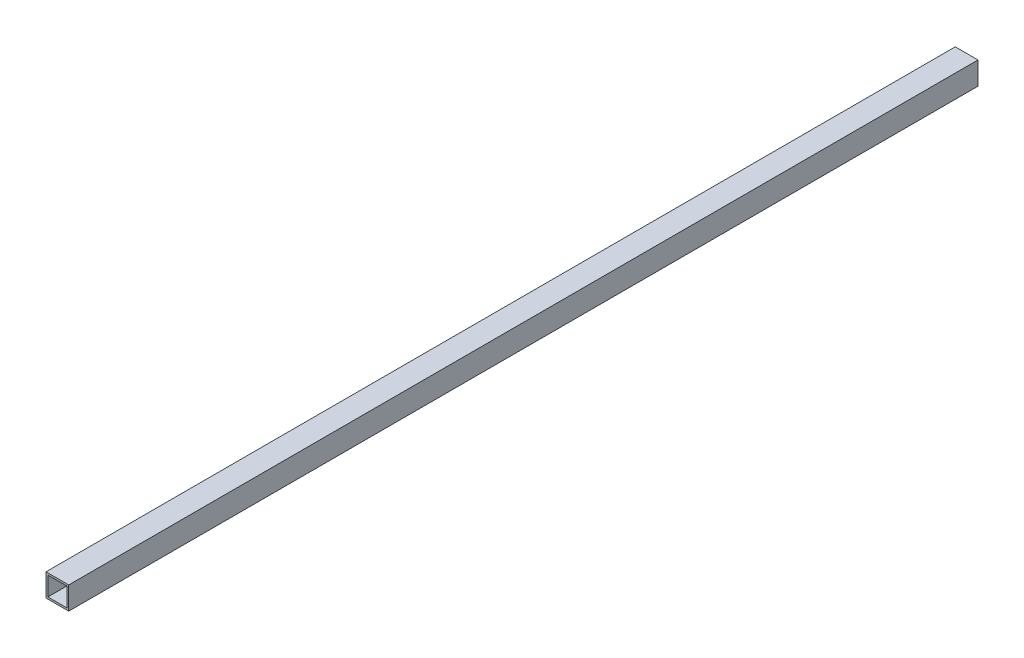
SolidWorks part; units mm, degrees
material "6063-T6"
ref_plane "Front Plane" through (0, 0, 0) normal (0, 0, 1) x (1, 0, 0)
ref_plane "Top Plane" through (0, 0, 0) normal (0, 1, 0) x (1, 0, 0)
ref_plane "Right Plane" through (0, 0, 0) normal (1, 0, 0) x (0, 0, -1)
sketch "Sketch1" plane through (0, 0, 0) normal (0, 0, 1) x (1, 0, 0)
  line L1 (9.525, -9.525) -> (-9.525, -9.525)
  line L2 (9.525, -9.525) -> (9.525, 9.525)
  line L3 (9.525, 9.525) -> (-9.525, 9.525)
  line L4 (-9.525, -9.525) -> (-9.525, 9.525)
  line L5 (9.525, -9.525) -> (-9.525, 9.525) construction
  line L6 (9.525, 9.525) -> (-9.525, -9.525) construction
  line L7 (7.9375, -7.9375) -> (-7.9375, -7.9375)
  line L8 (7.9375, -7.9375) -> (7.9375, 7.9375)
  line L9 (7.9375, 7.9375) -> (-7.9375, 7.9375)
  line L10 (-7.9375, -7.9375) -> (-7.9375, 7.9375)
  line L11 (7.9375, -7.9375) -> (-7.9375, 7.9375) construction
  line L12 (7.9375, 7.9375) -> (-7.9375, -7.9375) construction
  point P0 (0, 0)
  point P5 (0, 0)
  dimension "D1" = 19.05
  dimension "D2" = 19.05
  dimension "D3" = 1.5875
extrude "Boss-Extrude1" add sketch "Sketch1" along normal mid plane 762
